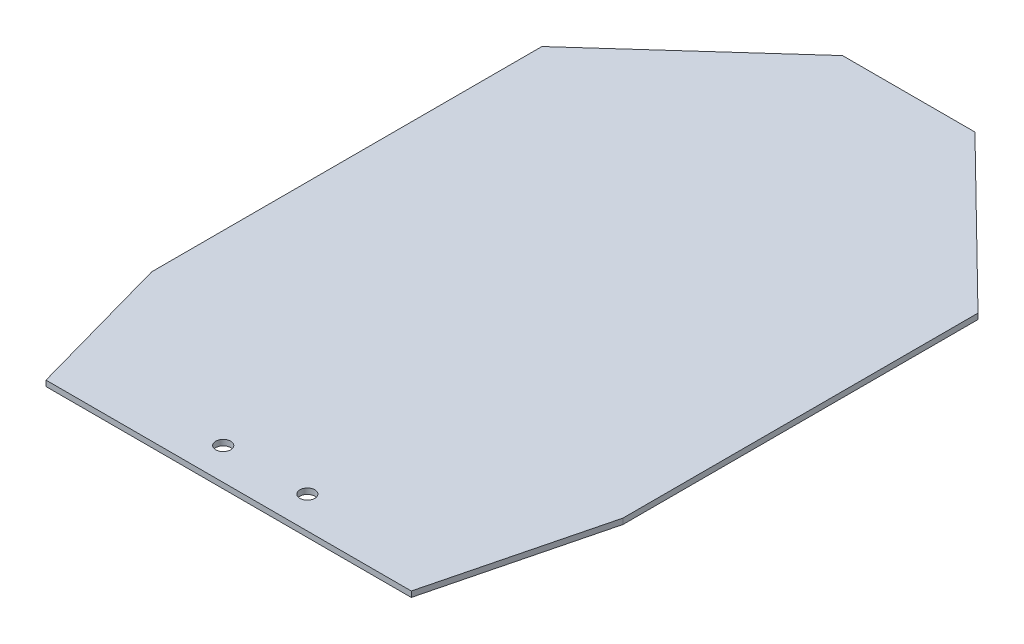
SolidWorks part; units mm, degrees
material "Copolímero acetal (POM)"
ref_plane "Plano frontal" through (0, 0, 0) normal (0, 0, 1) x (1, 0, 0)
ref_plane "Plano superior" through (0, 0, 0) normal (0, 1, 0) x (1, 0, 0)
ref_plane "Plano direito" through (0, 0, 0) normal (1, 0, 0) x (0, 0, -1)
sketch "Esboço1" plane through (0, 0, 0) normal (0, 1, 0) x (1, 0, 0)
  line L0 (97.2557, -182.75) -> (120.0798, -92.3879)
  line L1 (35.4, 180.55) -> (-35.4, 180.55)
  line L2 (-35.4, 180.55) -> (-119.9895, 104.35)
  line L3 (-119.9895, 104.35) -> (-119.9895, -104.35)
  line L4 (-119.9895, -104.35) -> (-98.0943, -182.75)
  line L5 (-98.0943, -182.75) -> (97.2557, -182.75)
  line L6 (120.0798, -92.3879) -> (120.0798, 97.5121)
  line L7 (120.0798, 97.5121) -> (35.4, 180.55)
  point P0 (0, 180.55)
  point P9 (-119.9895, 0)
  dimension "D1" = 208.7
  dimension "D2" = 81.4
  dimension "D3" = 113.85
  dimension "D4" = 70.8
  dimension "D5" = 195.35
  dimension "D6" = 93.2
  dimension "D7" = 189.9
  dimension "D8" = 118.6
  dimension "D9" = 78.4
  dimension "D10" = 76.2
extrude "Ressalto-extrusão1" add sketch "Esboço1" along normal blind 3
sketch "Esboço2" plane through (0, 3, 0) normal (0, 1, 0) x (1, 0, 0)
  line L0 (-98.0943, -182.75) -> (97.2557, -182.75) construction
  line L2 (120.0798, -92.3879) -> (120.0798, 97.5121) construction
  circle A0 centre (24.5798, -165.65) radius 4
  circle A1 centre (-20.4202, -165.65) radius 4
  dimension "D1" = 17.1
  dimension "D3" = 8
  dimension "D4" = 8
  dimension "D2" = 95.5
  dimension "D5" = 45
extrude "Corte-extrusão1" cut sketch "Esboço2" against normal through all
